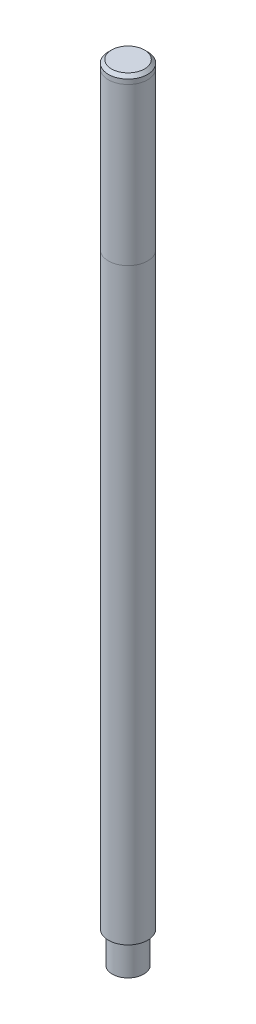
SolidWorks part; units mm, degrees
ref_plane "Front Plane" through (0, 0, 0) normal (0, 0, 1) x (1, 0, 0)
ref_plane "Top Plane" through (0, 0, 0) normal (0, 1, 0) x (1, 0, 0)
ref_plane "Right Plane" through (0, 0, 0) normal (1, 0, 0) x (0, 0, -1)
sketch "Sketch1" plane through (0, 0, 0) normal (0, 1, 0) x (1, 0, 0)
  circle A0 centre (0, 0) radius 12.5
  dimension "D1" = 25
extrude "Boss-Extrude1" add sketch "Sketch1" along normal mid plane 500
sketch "Sketch2" plane through (0, 0, 0) normal (0, 0, 1) x (1, 0, 0)
  line L0 (-46.307, 245) -> (67.1241, 245)
  line L1 (12.5, 250) -> (-12.5, 250) construction
  line L2 (-46.307, 245) -> (-46.307, 145)
  line L3 (-46.307, 145) -> (58.77, 145)
  dimension "D1" = 5
  dimension "D2" = 100
split line "Split Line1"
chamfer "Chamfer1" distance 2 angle 45 1 edges at (0, 250, 12.5)
sketch "Sketch3" plane through (0, -250, 0) normal (0, -1, 0) x (1, 0, 0)
  circle A0 centre (0, 0) radius 12.5
  circle A1 centre (0, 0) radius 10
extrude "Cut-Extrude1" cut sketch "Sketch3" against normal blind 20
